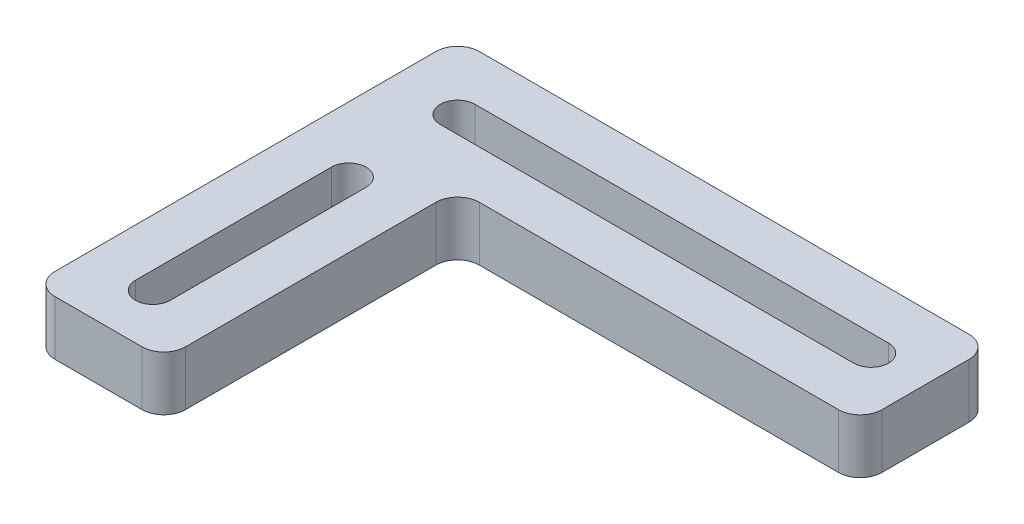
SolidWorks part; units mm, degrees
ref_plane "Front Plane" through (0, 0, 0) normal (0, 0, 1) x (1, 0, 0)
ref_plane "Top Plane" through (0, 0, 0) normal (0, 1, 0) x (1, 0, 0)
ref_plane "Right Plane" through (0, 0, 0) normal (1, 0, 0) x (0, 0, -1)
sketch "Sketch1" plane through (0, 0, 0) normal (0, 1, 0) x (1, 0, 0)
  line L0 (4, -2) -> (4, 3) construction
  line L1 (0, -2) -> (8, -2)
  line L2 (-2, 0) -> (-2, 35)
  line L3 (0, 37) -> (45, 37)
  line L4 (10, 0) -> (10, 23)
  line L5 (47, 35) -> (47, 27)
  line L6 (45, 25) -> (12, 25)
  line L7 (4, 3) -> (4, 21) construction
  line L8 (47, 31) -> (42, 31) construction
  line L9 (42, 31) -> (4, 31) construction
  line L10 (42, 29.4) -> (4, 29.4)
  line L11 (42, 32.6) -> (4, 32.6)
  line L12 (2.4, 3) -> (2.4, 21)
  line L13 (5.6, 3) -> (5.6, 21)
  arc A0 (0, -2) -> (-2, 0) centre (0, 0) cw
  arc A1 (8, -2) -> (10, 0) centre (8, 0) ccw
  arc A2 (12, 25) -> (10, 23) centre (12, 23) ccw
  arc A3 (47, 27) -> (45, 25) centre (45, 27) cw
  arc A4 (47, 35) -> (45, 37) centre (45, 35) ccw
  arc A5 (0, 37) -> (-2, 35) centre (0, 35) ccw
  arc A6 (2.4, 3) -> (5.6, 3) centre (4, 3) ccw
  arc A7 (5.6, 21) -> (2.4, 21) centre (4, 21) ccw
  arc A8 (42, 29.4) -> (42, 32.6) centre (42, 31) ccw
  arc A9 (4, 32.6) -> (4, 29.4) centre (4, 31) ccw
  point P6 (4, 12)
  point P27 (23, 31)
  dimension "D1" = 2
  dimension "D6" = 3.2
  dimension "D7" = 18
  dimension "D2" = 8
  dimension "D3" = 45
  dimension "D4" = 8
  dimension "D5" = 35
  dimension "D8" = 5
  dimension "D9" = 3.2
  dimension "D10" = 5
  dimension "D11" = 38
extrude "Boss-Extrude1" add sketch "Sketch1" along normal blind 5
